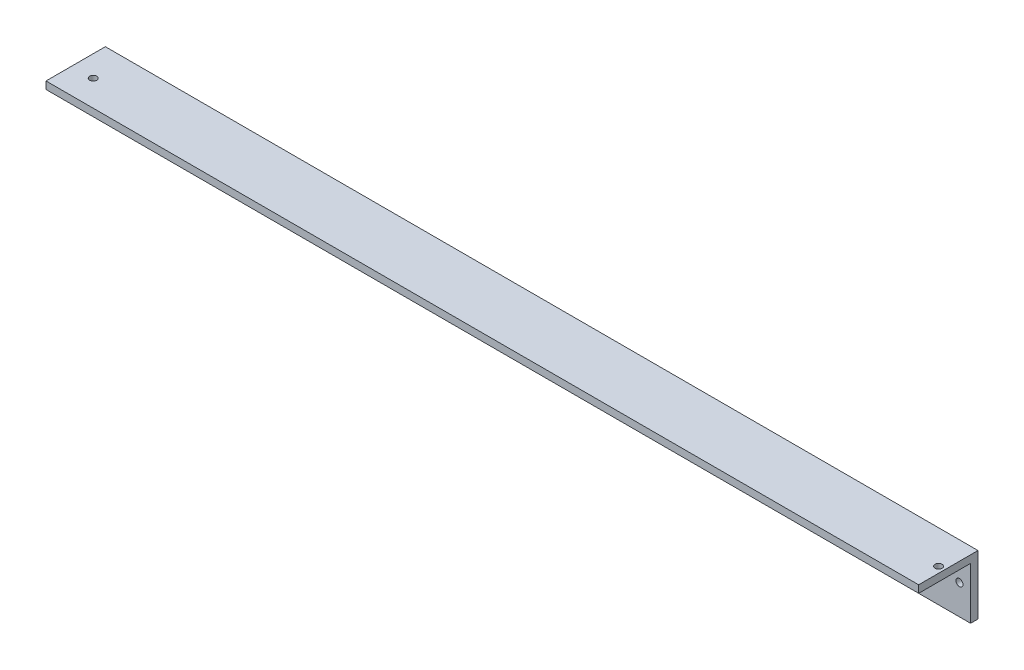
SolidWorks part; units mm, degrees
ref_plane "Alzado" through (0, 0, 0) normal (0, 0, 1) x (1, 0, 0)
ref_plane "Planta" through (0, 0, 0) normal (0, 1, 0) x (1, 0, 0)
ref_plane "Vista lateral" through (0, 0, 0) normal (1, 0, 0) x (0, 0, -1)
sketch "Croquis1" plane through (0, 0, 0) normal (0, 0, 1) x (1, 0, 0)
  line L0 (0, 0) -> (1206.08, 0)
  line L1 (1206.08, 0) -> (1206.08, 80)
  line L2 (1206.08, 80) -> (0, 80)
  line L3 (0, 80) -> (0, 0)
  line L4 (1206.08, 40) -> (1176.08, 40) construction
  line L5 (0, 40) -> (30, 40) construction
  circle A0 centre (30, 40) radius 4.7625
  circle A1 centre (1176.08, 40) radius 4.765
  dimension "D5" = 9.525
  dimension "D6" = 9.53
  dimension "D1" = 1206.08
  dimension "D2" = 80
  dimension "D3" = 30
  dimension "D4" = 30
extrude "Saliente-Extruir1" add sketch "Croquis1" along normal blind 10
sketch "Croquis2" plane through (0, 0, 10) normal (0, 0, 1) x (1, 0, 0)
  line L0 (0, 80) -> (1206.08, 80)
  line L1 (1206.08, 80) -> (1206.08, 70)
  line L2 (1206.08, 0) -> (1206.08, 80) construction
  line L3 (1206.08, 70) -> (0, 70)
  line L4 (0, 80) -> (0, 0) construction
  line L5 (0, 70) -> (0, 80)
  dimension "D1" = 10
extrude "Saliente-Extruir2" add sketch "Croquis2" along normal blind 70
sketch "Croquis3" plane through (0, 70, 0) normal (0, -1, 0) x (1, 0, 0)
  line L0 (0, 45) -> (43.6612, 45) construction
  line L1 (0, 80) -> (0, 10) construction
  line L2 (1206.08, 45) -> (1182.9568, 45) construction
  line L3 (1206.08, 80) -> (1206.08, 10) construction
  circle A0 centre (1182.9568, 45) radius 4.765
  circle A1 centre (43.6612, 45) radius 4.765
  dimension "D1" = 9.53
  dimension "D2" = 9.53
extrude "Cortar-Extruir1" cut sketch "Croquis3" against normal through all
sketch "Croquis4" plane through (1206.08, 0, 0) normal (1, 0, 0) x (0, 0, -1)
  line L0 (-10, 0) -> (0, 0)
  line L1 (0, 0) -> (0, 80)
  line L2 (0, 80) -> (-80, 80)
  line L3 (-80, 80) -> (-80, 70)
  line L4 (-80, 70) -> (-10, 70)
  line L5 (-10, 70) -> (-10, 0)
extrude "Cortar-Extruir2" cut sketch "Croquis4" against normal blind 15
sketch "Croquis5" plane through (0, 0, 0) normal (-1, 0, 0) x (0, 0, 1)
  line L0 (0, 80) -> (0, 0)
  line L1 (0, 0) -> (10, 0)
  line L2 (10, 0) -> (10, 70)
  line L3 (10, 70) -> (80, 70)
  line L4 (80, 70) -> (80, 80)
  line L5 (80, 80) -> (0, 80)
extrude "Cortar-Extruir3" cut sketch "Croquis5" against normal blind 15
